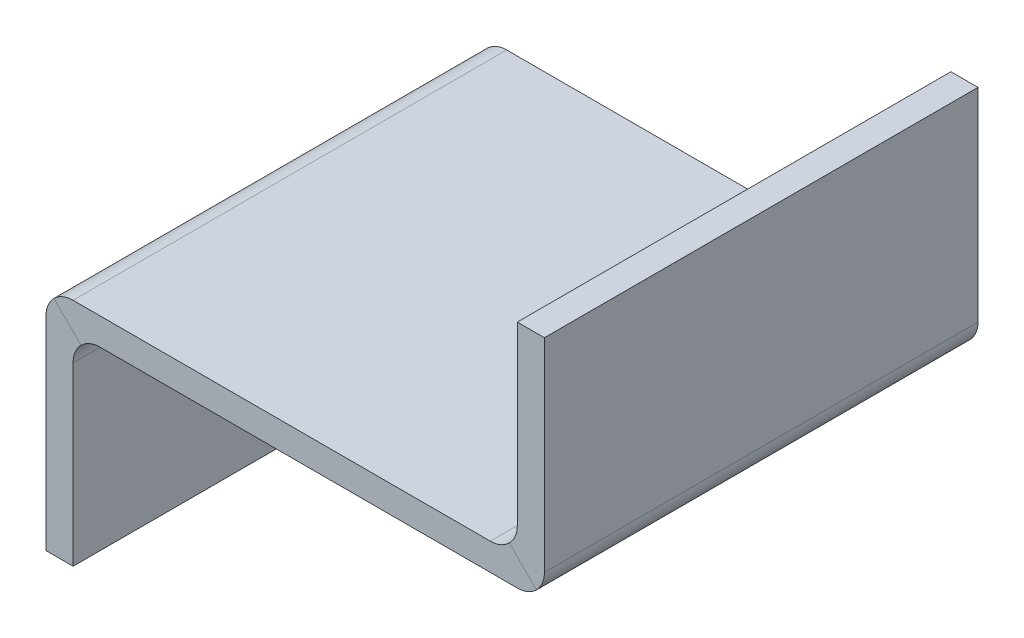
SolidWorks part; units mm, degrees
ref_plane "前视基准面" through (0, 0, 0) normal (0, 0, 1) x (1, 0, 0)
ref_plane "上视基准面" through (0, 0, 0) normal (0, 1, 0) x (1, 0, 0)
ref_plane "右视基准面" through (0, 0, 0) normal (1, 0, 0) x (0, 0, -1)
sketch "草图2" plane through (0, 0, 0) normal (1, 0, 0) x (0, 0, -1)
  line L1 (-20, -1.25) -> (20, -1.25)
  line L2 (-20, -1.25) -> (-20, 1.25)
  line L3 (-20, 1.25) -> (20, 1.25)
  line L4 (20, -1.25) -> (20, 1.25)
  line L5 (-20, -1.25) -> (20, 1.25) construction
  line L6 (-20, 1.25) -> (20, -1.25) construction
  point P0 (0, 0)
sketch "草图3" plane through (0, 0, 0) normal (0, 0, 1) x (1, 0, 0)
  line L0 (0, 0) -> (21.74, 0)
  line L1 (0, -1.25) -> (0, 1.25) construction
  line L2 (21.74, 0) -> (21.74, 20)
  line L3 (0, 0) -> (-21.74, 0)
  line L4 (-21.74, 0) -> (-21.74, -20)
  dimension "D1" = 20
  dimension "D2" = 21.74
  dimension "D3" = 21.74
  dimension "D4" = 20
sweep "扫描1" add profiles "草图2" path "草图3"
fillet "圆角1" radius 2.5 1 edges at (-22.99, 1.25, 0)
fillet "圆角2" radius 2.5 1 edges at (22.99, -1.25, 0)
fillet "圆角3" radius 2.5 2 edges at (20.49, 1.25, 0) (-20.49, -1.25, 0)
